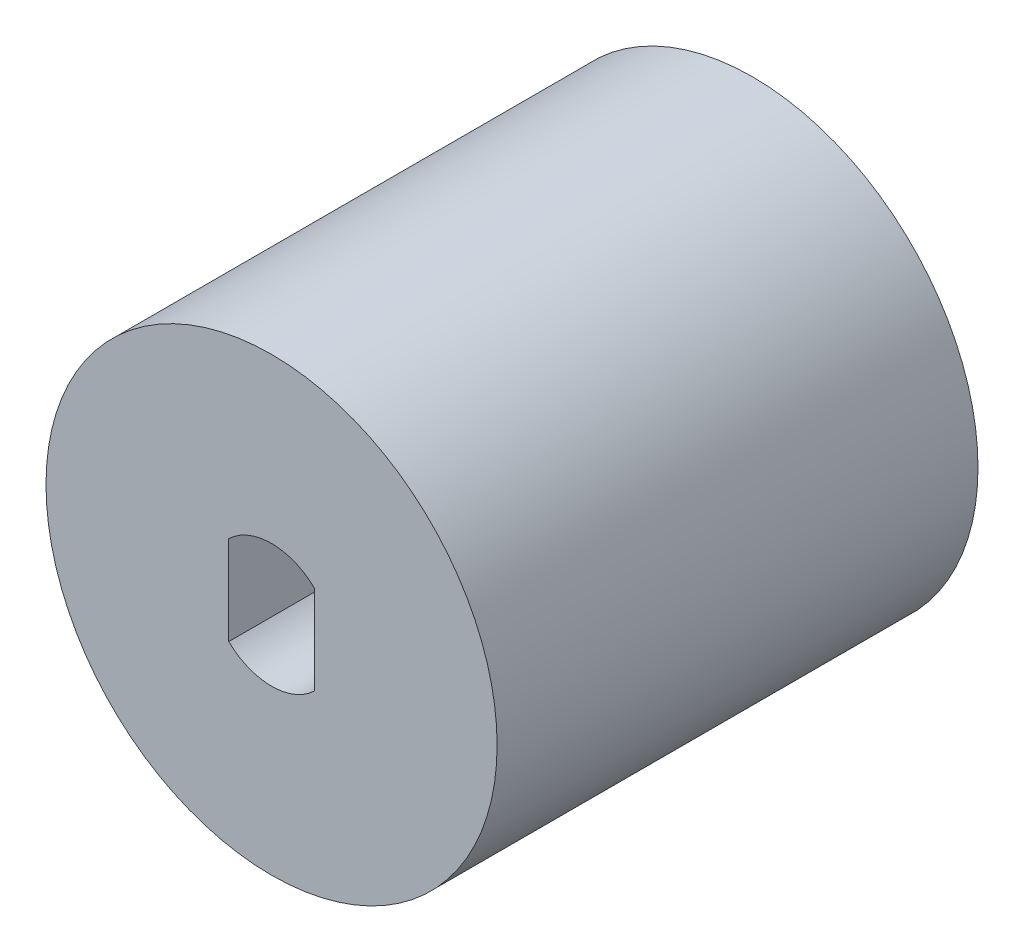
SolidWorks part; units mm, degrees
ref_plane "Alzado" through (0, 0, 0) normal (0, 0, 1) x (1, 0, 0)
ref_plane "Planta" through (0, 0, 0) normal (0, 1, 0) x (1, 0, 0)
ref_plane "Vista lateral" through (0, 0, 0) normal (1, 0, 0) x (0, 0, -1)
sketch "Croquis1" plane through (0, 0, 0) normal (0, 0, 1) x (1, 0, 0)
  circle A0 centre (0, 0) radius 9.85
  dimension "D1" = 19.7
extrude "Saliente-Extruir2" add sketch "Croquis1" along normal blind 21
sketch "Croquis2" plane through (0, 0, 0) normal (0, 0, 1) x (1, 0, 0)
  line L2 (-1.87, 1.9476) -> (-1.87, -1.9476)
  line L4 (1.87, 1.9476) -> (1.87, -1.9476)
  arc A0 (-1.87, -1.9476) -> (1.87, -1.9476) centre (0, 0) ccw
  arc A1 (1.87, 1.9476) -> (-1.87, 1.9476) centre (0, 0) ccw
  point P7 (0, 0)
  dimension "D1" = 5.4
  dimension "D2" = 3.74
extrude "Cortar-Extruir1" cut sketch "Croquis2" along normal up to surface (21 mm away) up to face at (9.85, 0, 21)
